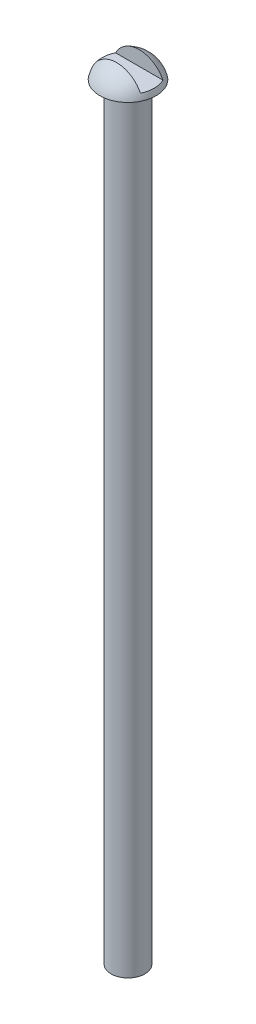
SolidWorks part; units mm, degrees
ref_plane "Front Plane" through (0, 0, 0) normal (0, 0, 1) x (1, 0, 0)
ref_plane "Top Plane" through (0, 0, 0) normal (0, 1, 0) x (1, 0, 0)
ref_plane "Right Plane" through (0, 0, 0) normal (1, 0, 0) x (0, 0, -1)
sketch "Esquisse1" plane through (0, 0, 0) normal (0, 0, 1) x (1, 0, 0)
  line L0 (0, 0) -> (0, 70) construction
  line L1 (2.5, 68) -> (1.5, 68)
  line L2 (1.5, 68) -> (1.5, 0)
  line L3 (1.5, 0) -> (0, 0)
  line L4 (0, 0) -> (0, 70)
  arc A0 (0, 70) -> (2.5, 68) centre (0, 67.4375) cw
  dimension "D1" = 70
  dimension "D2" = 1.5
  dimension "D3" = 2.5
  dimension "D4" = 68
revolve "Révolution1" add sketch "Esquisse1" angle 360 about L0
sketch "Esquisse2" plane through (0, 68, 0) normal (0, -1, 0) x (1, 0, 0)
  line L0 (2.5, 0) -> (-4.8031, 0) construction
  line L1 (0, -2.5) -> (0, 2.5) construction
  line L2 (2.5, 1) -> (-4.8031, 1)
  line L3 (2.5, -1) -> (-4.8031, -1)
  circle A0 centre (0, 0) radius 2.5 construction
  arc A1 (2.5, 1) -> (2.5, -1) centre (2.5, 0) cw
  arc A2 (-4.8031, 1) -> (-4.8031, -1) centre (-4.8031, 0) ccw
  dimension "D1" = 1
  dimension "D2" = 1
extrude "Enlèv. mat.-Extru.1" cut sketch "Esquisse2" against normal blind 10 from offset 0.5
